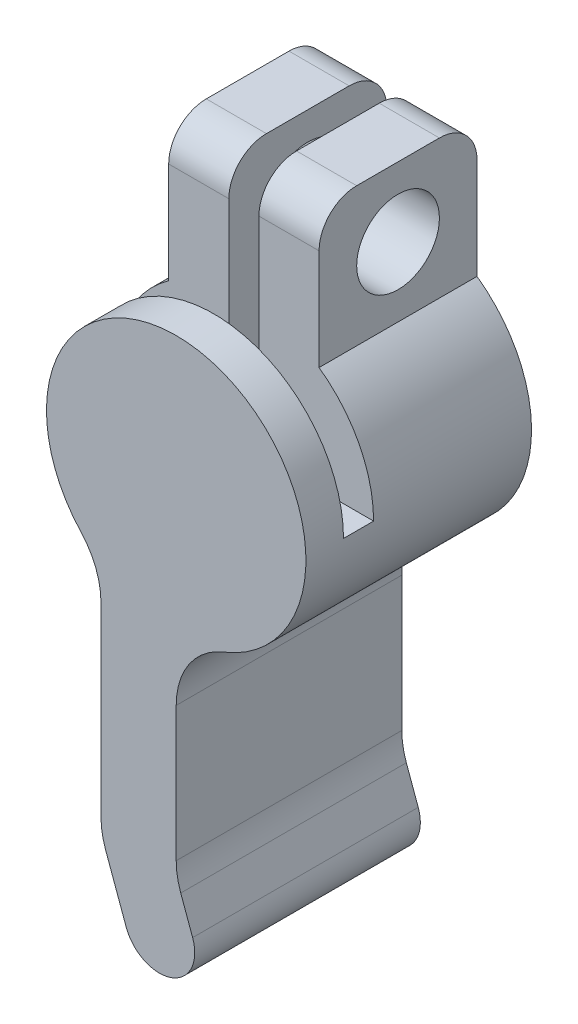
SolidWorks part; units mm, degrees
material "ABS"
ref_plane "Front Plane" through (0, 0, 0) normal (0, 0, 1) x (1, 0, 0)
ref_plane "Top Plane" through (0, 0, 0) normal (0, 1, 0) x (1, 0, 0)
ref_plane "Right Plane" through (0, 0, 0) normal (1, 0, 0) x (0, 0, -1)
sketch "Sketch1" plane through (0, 0, 0) normal (0, 0, 1) x (1, 0, 0)
  line L0 (0, -9) -> (0, -3.45)
  line L1 (-2, -9) -> (-2, -2.8111)
  line L2 (0, -9) -> (0.4368, -10.2)
  line L4 (-1.3293, -10.8428) -> (-2, -9)
  line L5 (-2, -9) -> (0, -9) construction
  line L6 (-1.3293, -10.8428) -> (0.4368, -10.2) construction
  line L9 (-0.4, 1.3937) -> (-0.4, 6.5)
  line L10 (-0.4, 6.5) -> (-2, 6.5)
  line L11 (-2, 6.5) -> (-2, 2.8111)
  line L12 (0.4, 1.3937) -> (0.4, 6.5)
  line L13 (0.4, 6.5) -> (2, 6.5)
  line L14 (2, 6.5) -> (2, 2.8111)
  arc A0 (-0.4, 1.3937) -> (0.4, 1.3937) centre (0, 0) ccw
  arc A2 (0, -3.45) -> (2, 2.8111) centre (0, 0) ccw
  circle A4 centre (0, 0) radius 3.45 construction
  arc A5 (-1.3293, -10.8428) -> (0.4368, -10.2) centre (-0.4463, -10.5214) ccw
  arc A6 (-2, 2.8111) -> (-2, -2.8111) centre (0, 0) ccw
  circle A7 centre (0, 0) radius 1.45 construction
  point P3 (-1, -9)
  dimension "D1" = 2.9
  dimension "D4" = 1.2
  dimension "D6" = 160
  dimension "D7" = 0.8
  dimension "D2" = 2
  dimension "D3" = 9
  dimension "D8" = 1.6
  dimension "D9" = 6.5
  dimension "D5" = 2
extrude "Boss-Extrude1" add sketch "Sketch1" along normal blind 4.2
sketch "Sketch2" plane through (-2, 0, 0) normal (-1, 0, 0) x (0, 0, 1)
  line L0 (4.2, 6.5) -> (0, 6.5) construction
  line L7 (0, 6.5) -> (0, 2.8111) construction
  circle A0 centre (2.1, 4.6556) radius 1.1
  point P2 (2.1, 6.5)
  point P3 (0, 4.6556)
  dimension "D1" = 2.2
extrude "Cut-Extrude1" cut sketch "Sketch2" against normal through all
fillet "Fillet1" radius 1 4 edges at (1.2, 6.5, 4.2) (1.2, 6.5, 0) (-1.2, 6.5, 4.2) (-1.2, 6.5, 0)
sketch "Sketch3" plane through (0, 0, 4.2) normal (0, 0, 1) x (1, 0, 0)
  line L0 (-3.45, 0) -> (-1.45, 0)
  line L1 (1.45, 0) -> (3.45, 0)
  line L10 (2, 2.8111) -> (2, 5.5)
  line L11 (2, 5.5) -> (0.4, 5.5)
  line L12 (0.4, 5.5) -> (0.4, 1.3937)
  line L13 (-0.4, 1.3937) -> (-0.4, 5.5)
  line L14 (-0.4, 5.5) -> (-2, 5.5)
  line L15 (-2, 5.5) -> (-2, 2.8111)
  line L16 (-2, -2.8111) -> (-2, -9)
  line L17 (-2, -9) -> (-1.3293, -10.8428)
  line L18 (0.4368, -10.2) -> (0, -9)
  line L19 (0, -9) -> (0, -3.45)
  line L22 (0.4, 5.5) -> (0.4, 1.3937)
  line L26 (-2, -2.8111) -> (-2, -9)
  line L27 (-2, -9) -> (-1.3293, -10.8428)
  line L28 (0.4368, -10.2) -> (0, -9)
  line L29 (0, -9) -> (0, -3.45)
  arc A4 (-0.4, 1.3937) -> (0.4, 1.3937) centre (0, 0) ccw
  arc A5 (-2, 2.8111) -> (-2, -2.8111) centre (0, 0) ccw
  arc A6 (-1.3293, -10.8428) -> (0.4368, -10.2) centre (-0.4463, -10.5214) ccw
  arc A7 (0, -3.45) -> (2, 2.8111) centre (0, 0) ccw
  arc A8 (-1.45, 0) -> (1.45, 0) centre (0, 0) ccw
  arc A9 (-3.45, 0) -> (-2, -2.8111) centre (0, 0) ccw
  arc A10 (-1.3293, -10.8428) -> (0.4368, -10.2) centre (-0.4463, -10.5214) ccw
  arc A11 (0, -3.45) -> (3.45, 0) centre (0, 0) ccw
  arc M18 (0.4, 1.3937) -> (-0.4, 1.3937) centre (0, 0) cw
  arc M22 (-2, 2.8111) -> (-2, -2.8111) centre (0, 0) ccw
  line M23 (-2, -2.8111) -> (-2, -9)
  line M24 (-2, -9) -> (-1.3293, -10.8428)
  arc M25 (-1.3293, -10.8428) -> (0.4368, -10.2) centre (-0.4463, -10.5214) ccw
  line M26 (0.4368, -10.2) -> (0, -9)
  line M27 (0, -9) -> (0, -3.45)
  arc M28 (0, -3.45) -> (2, 2.8111) centre (0, 0) ccw
  dimension "D1" = 0
extrude "Boss-Extrude2" add sketch "Sketch3" along normal blind 0.8 contours L1 L0 M18 M22 M23 M24 M25 M26 M27 M28
sketch "Sketch4" plane through (0, 0, 5) normal (0, 0, 1) x (1, 0, 0)
  line L4 (1.45, 0) -> (3.45, 0)
  line L5 (2, 2.8111) -> (2, 5.5)
  line L6 (3.45, 0) -> (1.45, 0)
  line L7 (-1.45, 0) -> (-3.45, 0)
  line L8 (-2, -2.8111) -> (-2, -9)
  line L9 (-2, -9) -> (-1.3293, -10.8428)
  line L10 (0.4368, -10.2) -> (0, -9)
  line L11 (0, -9) -> (0, -3.45)
  line L14 (-2, -2.8111) -> (-2, -9)
  line L15 (-2, -9) -> (-1.3293, -10.8428)
  line L16 (0.4368, -10.2) -> (0, -9)
  line L17 (0, -9) -> (0, -3.45)
  line L18 (2, 5.5) -> (0.4, 5.5)
  line L19 (0.4, 5.5) -> (0.4, 1.3937)
  line L24 (-3.45, 0) -> (-1.45, 0)
  line L25 (-0.4, 1.3937) -> (-0.4, 5.5)
  line L26 (-0.4, 5.5) -> (-2, 5.5)
  line L27 (-2, 5.5) -> (-2, 2.8111)
  arc A2 (3.45, 0) -> (2, 2.8111) centre (0, 0) ccw
  arc A3 (1.45, 0) -> (0.4, 1.3937) centre (0, 0) ccw
  arc A4 (-1.45, 0) -> (1.45, 0) centre (0, 0) ccw
  arc A5 (-3.45, 0) -> (-2, -2.8111) centre (0, 0) ccw
  arc A6 (-1.3293, -10.8428) -> (0.4368, -10.2) centre (-0.4463, -10.5214) ccw
  arc A7 (0, -3.45) -> (3.45, 0) centre (0, 0) ccw
  arc A8 (-1.45, 0) -> (1.45, 0) centre (0, 0) ccw
  arc A9 (-3.45, 0) -> (-2, -2.8111) centre (0, 0) ccw
  arc A10 (-1.3293, -10.8428) -> (0.4368, -10.2) centre (-0.4463, -10.5214) ccw
  arc A11 (0, -3.45) -> (3.45, 0) centre (0, 0) ccw
  arc A12 (3.45, 0) -> (2, 2.8111) centre (0, 0) ccw
  arc A13 (1.45, 0) -> (0.4, 1.3937) centre (0, 0) ccw
  arc A14 (-0.4, 1.3937) -> (-1.45, 0) centre (0, 0) ccw
  arc A15 (-2, 2.8111) -> (-3.45, 0) centre (0, 0) ccw
  arc A16 (0.4, 1.3937) -> (-1.45, 0) centre (0, 0) ccw
  arc A17 (2, 2.8111) -> (-3.45, 0) centre (0, 0) ccw
  line M23 (3.45, 0) -> (1.45, 0)
  arc M24 (1.45, 0) -> (-1.45, 0) centre (0, 0) cw
  line M25 (-1.45, 0) -> (-3.45, 0)
  arc M26 (-3.45, 0) -> (-2, -2.8111) centre (0, 0) ccw
  line M27 (-2, -2.8111) -> (-2, -9)
  line M28 (-2, -9) -> (-1.3293, -10.8428)
  arc M29 (-1.3293, -10.8428) -> (0.4368, -10.2) centre (-0.4463, -10.5214) ccw
  line M30 (0.4368, -10.2) -> (0, -9)
  line M31 (0, -9) -> (0, -3.45)
  arc M32 (0, -3.45) -> (3.45, 0) centre (0, 0) ccw
  dimension "D1" = 0
  dimension "D2" = 0
  dimension "D3" = 0
extrude "Boss-Extrude3" add sketch "Sketch4" along normal blind 1 contours A13 A16 M24 | A12 A17 A16 A13 M25 M23 | M32 M23 M24 M25 M26 M27 M28 M29 M30 M31
fillet "Fillet2" radius 2 4 edges at (-2, -9, 3) (0, -9, 3) (0, -3.45, 3) (-2, -2.8111, 3)
